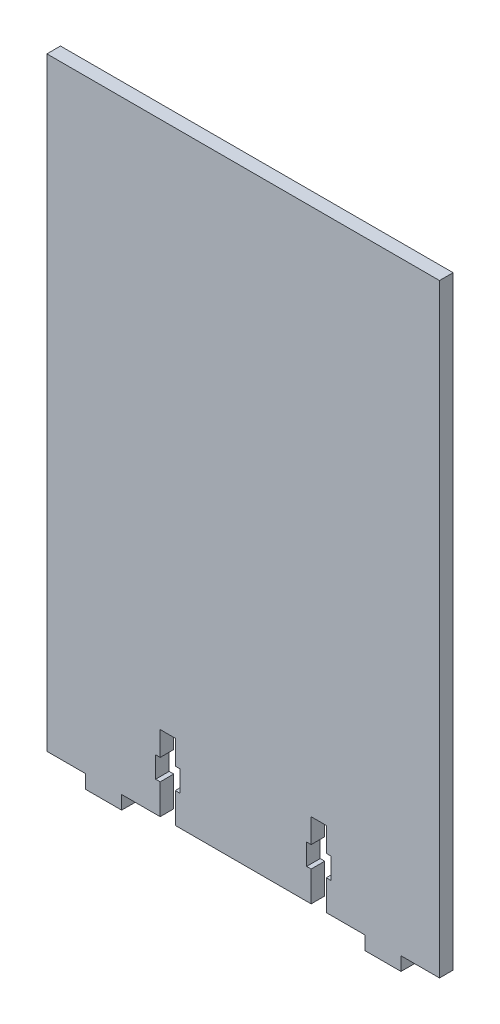
SolidWorks part; units mm, degrees
ref_plane "Front Plane" through (0, 0, 0) normal (0, 0, 1) x (1, 0, 0)
ref_plane "Top Plane" through (0, 0, 0) normal (0, 1, 0) x (1, 0, 0)
ref_plane "Right Plane" through (0, 0, 0) normal (1, 0, 0) x (0, 0, -1)
sketch "Sketch1" plane through (0, 0, 0) normal (0, 0, 1) x (1, 0, 0)
  line L1 (-65, 100) -> (65, 100)
  line L2 (-65, 100) -> (-65, -100)
  line L3 (-65, -100) -> (65, -100)
  line L4 (65, 100) -> (65, -100)
  line L5 (-65, 100) -> (65, -100) construction
  line L6 (-65, -100) -> (65, 100) construction
  point P0 (0, 0)
  dimension "D1" = 200
  dimension "D2" = 130
extrude "Boss-Extrude1" add sketch "Sketch1" along normal blind 4.5
sketch "Sketch2" plane through (0, 0, 4.5) normal (0, 0, 1) x (1, 0, 0)
  line L4 (-27.5, -100) -> (-27.5, -90)
  line L5 (-27.5, -90) -> (-29, -90)
  line L6 (-29, -90) -> (-29, -83)
  line L7 (-29, -83) -> (-27.5, -83)
  line L8 (65, -100) -> (65, 100)
  line L9 (65, 100) -> (-65, 100)
  line L10 (-65, 100) -> (-65, -100)
  line L11 (-65, -100) -> (65, -100)
  line L12 (65, -100) -> (65, 100)
  line L13 (65, 100) -> (-65, 100)
  line L14 (-65, 100) -> (-65, -100)
  line L15 (-65, -100) -> (65, -100)
  line L16 (-27.5, -83) -> (-27.5, -75)
  line L17 (-27.5, -75) -> (-22.5, -75)
  line L18 (-22.5, -75) -> (-22.5, -83)
  line L19 (-22.5, -83) -> (-21, -83)
  line L20 (-21, -83) -> (-21, -90)
  line L21 (-21, -90) -> (-22.5, -90)
  line L22 (-22.5, -90) -> (-22.5, -100)
  line L23 (-22.5, -100) -> (-27.5, -100)
  point P16 (-25, -75)
  line M20 (-65, -100) -> (65, -100)
  dimension "D2" = 5
  dimension "D3" = 7
  dimension "D4" = 40
  dimension "D5" = 8
  dimension "D6" = 25
  dimension "D7" = 10
  dimension "D1" = 0
extrude "Cut-Extrude1" cut sketch "Sketch2" against normal through all contours L22 L21 L20 L19 L18 L17 L16 L7 L6 L5 L4 M20
mirror "Mirror1" about plane through (0, 0, 0) normal (1, 0, 0) of "Cut-Extrude1"
sketch "Sketch3" plane through (0, 0, 4.5) normal (0, 0, 1) x (1, 0, 0)
  line L0 (0, -2.475) -> (0, 2.475) construction
  line L1 (-52.25, -100) -> (-40.25, -100)
  line L2 (-52.25, -100) -> (-52.25, -104.5)
  line L3 (-52.25, -104.5) -> (-40.25, -104.5)
  line L4 (-40.25, -100) -> (-40.25, -104.5)
  line L5 (-6, -100) -> (6, -100)
  line L6 (-6, -100) -> (-6, -104.5)
  line L7 (-6, -104.5) -> (6, -104.5)
  line L8 (6, -100) -> (6, -104.5)
  line L9 (52.25, -104.5) -> (40.25, -104.5)
  line L10 (40.25, -100) -> (40.25, -104.5)
  line L11 (52.25, -100) -> (40.25, -100)
  line L12 (52.25, -100) -> (52.25, -104.5)
  line L28 (22.5, -100) -> (22.5, -90)
  line L29 (22.5, -90) -> (21, -90)
  line L30 (21, -90) -> (21, -83)
  line L31 (21, -83) -> (22.5, -83)
  line L32 (22.5, -83) -> (22.5, -75)
  line L33 (22.5, -75) -> (27.5, -75)
  line L34 (27.5, -75) -> (27.5, -83)
  line L35 (27.5, -83) -> (29, -83)
  line L36 (29, -83) -> (29, -90)
  line L37 (29, -90) -> (27.5, -90)
  line L38 (27.5, -90) -> (27.5, -100)
  line L39 (27.5, -100) -> (65, -100)
  line L40 (65, -100) -> (65, 100)
  line L41 (65, 100) -> (-65, 100)
  line L42 (-65, 100) -> (-65, -100)
  line L43 (-65, -100) -> (-27.5, -100)
  line L44 (-27.5, -100) -> (-27.5, -90)
  line L45 (-27.5, -90) -> (-29, -90)
  line L46 (-29, -90) -> (-29, -83)
  line L47 (-29, -83) -> (-27.5, -83)
  line L48 (-27.5, -83) -> (-27.5, -75)
  line L49 (-27.5, -75) -> (-22.5, -75)
  line L50 (-22.5, -75) -> (-22.5, -83)
  line L51 (-22.5, -83) -> (-21, -83)
  line L52 (-21, -83) -> (-21, -90)
  line L53 (-21, -90) -> (-22.5, -90)
  line L54 (-22.5, -90) -> (-22.5, -100)
  line L55 (-22.5, -100) -> (22.5, -100)
  line L56 (22.5, -100) -> (22.5, -90)
  line L57 (22.5, -90) -> (21, -90)
  line L58 (21, -90) -> (21, -83)
  line L59 (21, -83) -> (22.5, -83)
  line L60 (22.5, -83) -> (22.5, -75)
  line L61 (22.5, -75) -> (27.5, -75)
  line L62 (27.5, -75) -> (27.5, -83)
  line L63 (27.5, -83) -> (29, -83)
  line L64 (29, -83) -> (29, -90)
  line L65 (29, -90) -> (27.5, -90)
  line L66 (27.5, -90) -> (27.5, -100)
  line L67 (27.5, -100) -> (65, -100)
  line L68 (65, -100) -> (65, 100)
  line L69 (65, 100) -> (-65, 100)
  line L70 (-65, 100) -> (-65, -100)
  line L71 (-65, -100) -> (-27.5, -100)
  line L72 (-27.5, -100) -> (-27.5, -90)
  line L73 (-27.5, -90) -> (-29, -90)
  line L74 (-29, -90) -> (-29, -83)
  line L75 (-29, -83) -> (-27.5, -83)
  line L76 (-27.5, -83) -> (-27.5, -75)
  line L77 (-27.5, -75) -> (-22.5, -75)
  line L78 (-22.5, -75) -> (-22.5, -83)
  line L79 (-22.5, -83) -> (-21, -83)
  line L80 (-21, -83) -> (-21, -90)
  line L81 (-21, -90) -> (-22.5, -90)
  line L82 (-22.5, -90) -> (-22.5, -100)
  line L83 (-22.5, -100) -> (22.5, -100)
  point P18 (-46.25, -100)
  point P20 (-46.25, -104.5)
  point P22 (0, -100)
  point P24 (0, -104.5)
  line M48 (27.5, -100) -> (65, -100)
  line M52 (-65, -100) -> (-27.5, -100)
  dimension "D2" = 4.5
  dimension "D3" = 12
  dimension "D1" = 0
extrude "Boss-Extrude2" add sketch "Sketch3" against normal up to surface (4.5 mm away) contours L4 L2 L3 M52 | L12 L10 L9 M48 up to face at (0, -74.4286, 0)
